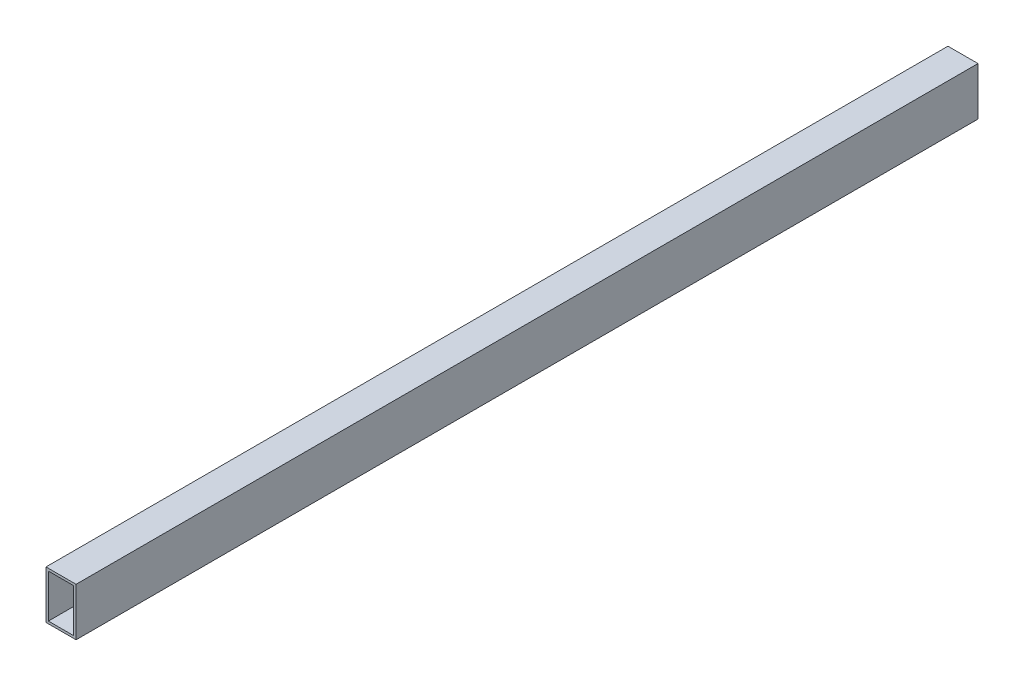
SolidWorks part; units mm, degrees
ref_plane "Front Plane" through (0, 0, 0) normal (0, 0, 1) x (1, 0, 0)
ref_plane "Top Plane" through (0, 0, 0) normal (0, 1, 0) x (1, 0, 0)
ref_plane "Right Plane" through (0, 0, 0) normal (1, 0, 0) x (0, 0, -1)
sketch "Sketch1" plane through (0, 0, 0) normal (0, 0, 1) x (1, 0, 0)
  line L1 (-25, 40) -> (25, 40)
  line L2 (-25, 40) -> (-25, -40)
  line L3 (-25, -40) -> (25, -40)
  line L4 (25, 40) -> (25, -40)
  point P0 (0, 0)
  point P7 (0, 0)
  dimension "D1" = 80
  dimension "D2" = 50
extrude "Boss-Extrude1" add sketch "Sketch1" along normal blind 1500 contours L1 L4 L3 L2
sketch "Sketch2" plane through (0, 0, 0) normal (0, 0, -1) x (-1, 0, 0)
  line L1 (-21, 36) -> (21, 36)
  line L2 (-21, 36) -> (-21, -36)
  line L3 (-21, -36) -> (21, -36)
  line L4 (21, 36) -> (21, -36)
  line L5 (-21, 36) -> (21, -36) construction
  line L6 (-21, -36) -> (21, 36) construction
  point P0 (0, 0)
  dimension "D1" = 42
  dimension "D2" = 72
extrude "Cut-Extrude1" cut sketch "Sketch2" against normal blind 1500
